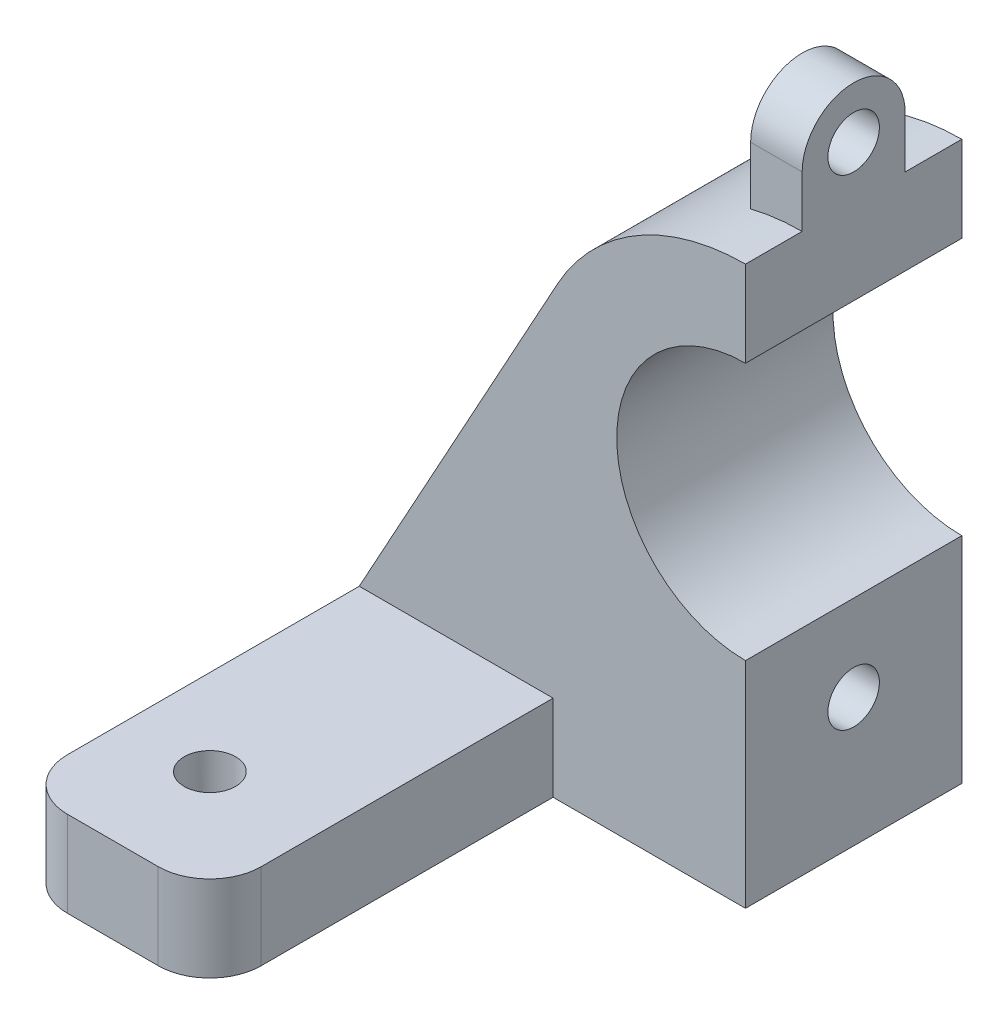
SolidWorks part; units mm, degrees
ref_plane "前视基准面" through (0, 0, 0) normal (0, 0, 1) x (1, 0, 0)
ref_plane "上视基准面" through (0, 0, 0) normal (0, 1, 0) x (1, 0, 0)
ref_plane "右视基准面" through (0, 0, 0) normal (1, 0, 0) x (0, 0, -1)
other "Configuration Table"
sketch "草图1" plane through (0, 0, 0) normal (0, 0, 1) x (1, 0, 0)
  line L0 (-10.9562, 6.0176) -> (-22.5, -15)
  line L1 (-22.5, -15) -> (-22.5, -20)
  line L2 (-22.5, -20) -> (22.5, -20)
  line L3 (0, 0) -> (0, -50000) construction
  line L4 (22.5, -15) -> (22.5, -20)
  line L5 (10.9562, 6.0176) -> (22.5, -15)
  circle A0 centre (0, 0) radius 7.5
  arc A1 (10.9562, 6.0176) -> (-10.9562, 6.0176) centre (0, 0) ccw
  point P11 (0, -20)
  dimension "D1" = 25
  dimension "D2" = 15
  dimension "D3" = 45
  dimension "D4" = 5
  dimension "D5" = 20
extrude "凸台-拉伸1" add sketch "草图1" along normal blind 12.6
sketch "草图2" plane through (0, 0, 0) normal (0, 0, 1) x (1, 0, 0)
  line L0 (-22.5, -15) -> (-11.2083, -15)
  line L1 (-11.2083, -15) -> (-11.2083, -20)
  line L2 (-22.5, -20) -> (22.5, -20) construction
  line L3 (-11.2083, -20) -> (-22.5, -20)
  line L4 (-22.5, -20) -> (-22.5, -15)
  line L5 (0, 0) -> (0, -50000) construction
  line L6 (22.5, -20) -> (22.5, -15)
  line L7 (11.2083, -20) -> (22.5, -20)
  line L8 (11.2083, -15) -> (11.2083, -20)
  line L9 (22.5, -15) -> (11.2083, -15)
extrude "凸台-拉伸2" add sketch "草图2" along normal blind 32.6
sketch "草图3" plane through (0, 0, 0) normal (0, 1, 0) x (1, 0, 0)
  line L0 (0, 0) -> (0, -50000) construction
  line L1 (-11.2083, -32.6) -> (-22.5, -32.6) construction
  circle A0 centre (-17.5, -26.3) radius 1.5
  circle A1 centre (17.5, -26.3) radius 1.5
  dimension "D1" = 3
  dimension "D2" = 6.3
  dimension "D3" = 35
extrude "切除-拉伸1" cut sketch "草图3" against normal through all
fillet "圆角1" radius 3 3 edges at (11.2083, -17.5, 32.6) (-11.2083, -17.5, 32.6) (-22.5, -17.5, 32.6)
sketch "草图4" plane through (0, 0, 0) normal (0, 1, 0) x (1, 0, 0)
  line L0 (22.5, -17.6) -> (22.5, -32.6)
  line L1 (22.5, -32.6) -> (22.5, -12.6) construction
  line L2 (22.5, -32.6) -> (25.5, -32.6)
  line L3 (25.5, -32.6) -> (25.5, -17.6)
  line L4 (25.5, -17.6) -> (22.5, -17.6)
  dimension "D1" = 3
  dimension "D2" = 15
extrude "凸台-拉伸3" add sketch "草图4" against normal through all
sketch "草图5" plane through (0, 0, 0) normal (1, 0, 0) x (0, 0, -1)
  line L0 (-25.1, 0) -> (-25.1, -50000) construction
  line L1 (-32.6, 0) -> (-17.6, 0) construction
  circle A0 centre (-25.1, -3) radius 1.3
  circle A1 centre (-25.1, -12.5) radius 1.3
  point P4 (-25.1, 0)
  dimension "D1" = 2.6
  dimension "D2" = 2.6
  dimension "D3" = 9.5
  dimension "D4" = 0
  dimension "D5" = 3
extrude "切除-拉伸2" cut sketch "草图5" along normal through all
sketch "草图6" plane through (0, 0, 0) normal (1, 0, 0) x (0, 0, -1)
  line L1 (-33.7604, 13.356) -> (2.2424, 13.356)
  line L2 (-33.7604, 13.356) -> (-33.7604, -21.3783)
  line L3 (-33.7604, -21.3783) -> (2.2424, -21.3783)
  line L4 (2.2424, 13.356) -> (2.2424, -21.3783)
extrude "切除-拉伸3" cut sketch "草图6" along normal through all
sketch "草图7" plane through (0, 0, 0) normal (1, 0, 0) x (0, 0, -1)
  line L0 (-6.3, 12.5) -> (-6.3, -49987.5) construction
  line L1 (0, 12.5) -> (-12.6, 12.5) construction
  line L2 (-9.3, 7.5) -> (-9.3, 12.5)
  line L3 (0, 7.5) -> (-12.6, 7.5) construction
  line L4 (-9.3, 12.5) -> (-9.3, 15.5)
  line L5 (-3.3, 15.5) -> (-3.3, 7.5)
  line L6 (-3.3, 7.5) -> (-9.3, 7.5)
  arc A0 (-9.3, 15.5) -> (-3.3, 15.5) centre (-6.3, 15.5) cw
  circle A1 centre (-6.3, 15.5) radius 1.5
  point P4 (-6.3, 12.5)
  dimension "D1" = 3
  dimension "D2" = 3
  dimension "D3" = 3
extrude "凸台-拉伸4" add sketch "草图7" against normal blind 3
sketch "草图8" plane through (0, 0, 0) normal (1, 0, 0) x (0, 0, -1)
  line L0 (-6.3, 7.5) -> (-6.3, -49992.5) construction
  line L1 (0, 7.5) -> (-12.6, 7.5) construction
  line L2 (0, 12.5) -> (-3.3, 12.5) construction
  circle A0 centre (-6.3, -12.5) radius 1.5
  point P4 (-6.3, 7.5)
  dimension "D1" = 3
  dimension "D2" = 25
extrude "切除-拉伸4" cut sketch "草图8" against normal through all
ref_plane "基准面1" through (-22.5, 0, 0) normal (1, 0, 0) x (0, 0, -1)
sketch "草图9" plane through (-22.5, 0, 0) normal (1, 0, 0) x (0, 0, -1)
  circle A0 centre (-6.3, -12.5) radius 3
  dimension "D1" = 6
extrude "切除-拉伸5" cut sketch "草图9" along normal blind 4
